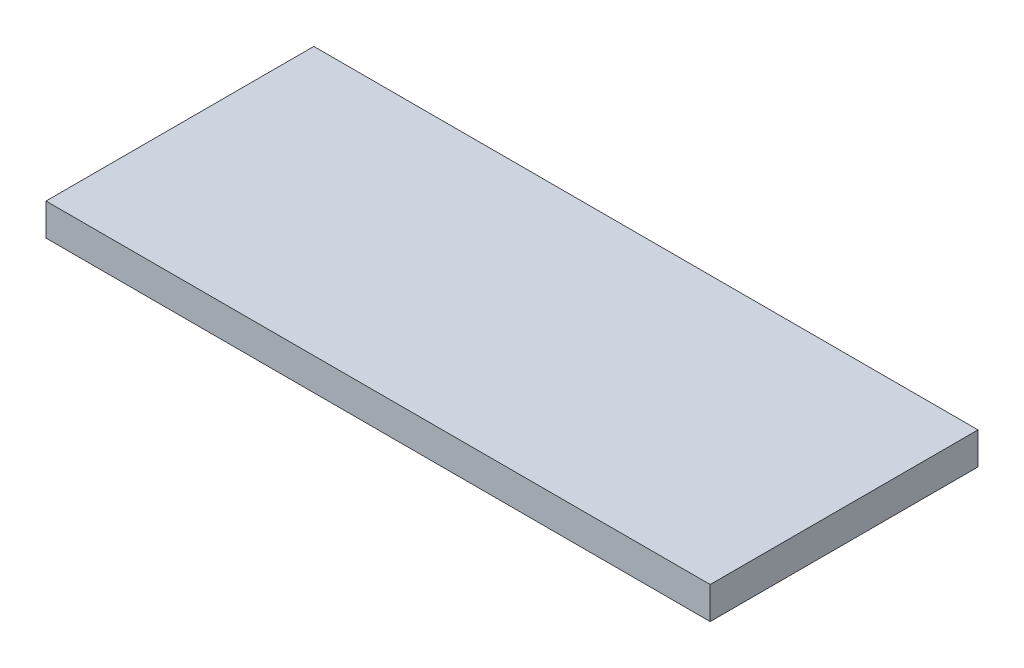
SolidWorks part; units mm, degrees
ref_plane "Plan de face" through (0, 0, 0) normal (0, 0, 1) x (1, 0, 0)
ref_plane "Plan de dessus" through (0, 0, 0) normal (0, 1, 0) x (1, 0, 0)
ref_plane "Plan de droite" through (0, 0, 0) normal (1, 0, 0) x (0, 0, -1)
sketch "Esquisse1" plane through (0, 0, 0) normal (0, 1, 0) x (1, 0, 0)
  line L1 (31, 12.5) -> (-31, 12.5)
  line L2 (31, 12.5) -> (31, -12.5)
  line L3 (31, -12.5) -> (-31, -12.5)
  line L4 (-31, 12.5) -> (-31, -12.5)
  line L5 (31, 12.5) -> (-31, -12.5) construction
  line L6 (31, -12.5) -> (-31, 12.5) construction
  point P0 (0, 0)
  dimension "D1" = 62
  dimension "D2" = 25
extrude "Boss.-Extru.1" add sketch "Esquisse1" along normal blind 3
